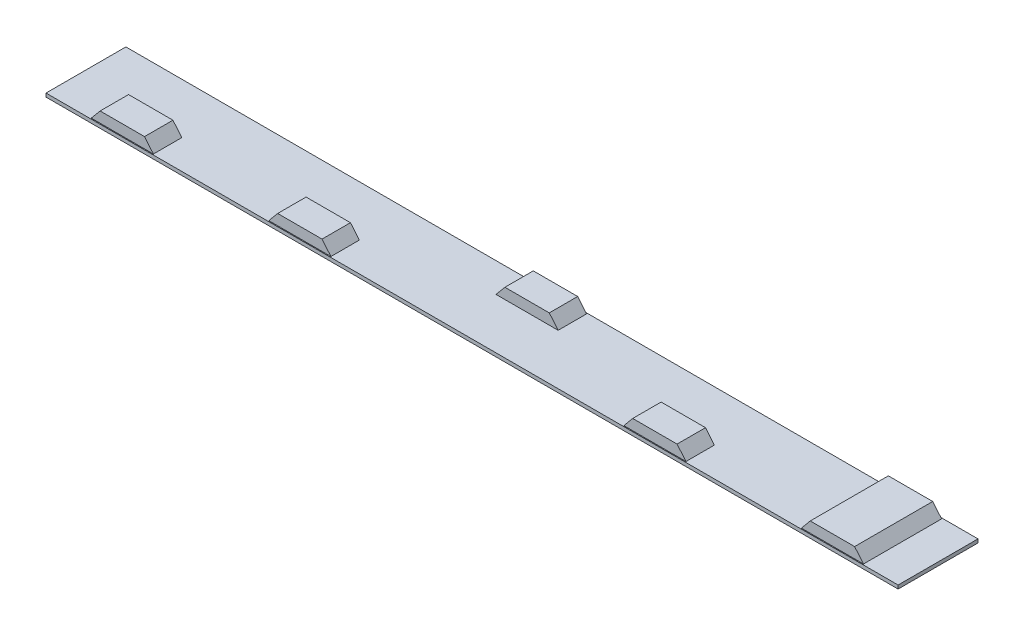
SolidWorks part; units mm, degrees
ref_plane "Front Plane" through (0, 0, 0) normal (0, 0, 1) x (1, 0, 0)
ref_plane "Top Plane" through (0, 0, 0) normal (0, 1, 0) x (1, 0, 0)
ref_plane "Right Plane" through (0, 0, 0) normal (1, 0, 0) x (0, 0, -1)
sketch "Sketch1" plane through (0, 0, 0) normal (0, 1, 0) x (1, 0, 0)
  line L1 (1200, 112.5) -> (-1200, 112.5)
  line L2 (1200, 112.5) -> (1200, -112.5)
  line L3 (1200, -112.5) -> (-1200, -112.5)
  line L4 (-1200, 112.5) -> (-1200, -112.5)
  line L5 (1200, 112.5) -> (-1200, -112.5) construction
  line L6 (1200, -112.5) -> (-1200, 112.5) construction
  point P0 (0, 0)
  dimension "D1" = 2400
  dimension "D2" = 225
extrude "Boss-Extrude1" add sketch "Sketch1" along normal blind 10
sketch "Sketch4" plane through (0, 0, 0) normal (0, 0, 1) x (1, 0, 0)
  line L0 (425, 10) -> (600, 10) construction
  line L1 (-1200, 10) -> (1200, 10) construction
  line L2 (600, 10) -> (575, 40) construction
  line L3 (575, 40) -> (450, 40) construction
  line L4 (450, 40) -> (425, 10) construction
  line L5 (-1075, 10) -> (-900, 10)
  line L6 (-900, 10) -> (-925, 40)
  line L7 (-925, 40) -> (-1050, 40)
  line L8 (-1050, 40) -> (-1075, 10)
  point P4 (512.5, 40)
  point P7 (512.5, 10)
  dimension "D1" = 175
  dimension "D2" = 125
  dimension "D3" = 30
  dimension "D4" = 600
  dimension "D5" = 2
extrude "Boss-Extrude3" add sketch "Sketch4" along normal blind 80 from offset 30
sketch "Sketch5" plane through (0, 0, 0) normal (0, 0, 1) x (1, 0, 0)
  line L0 (-75, 10) -> (100, 10)
  line L1 (100, 10) -> (75, 40)
  line L2 (75, 40) -> (-50, 40)
  line L3 (-50, 40) -> (-75, 10)
  line L4 (-1075, 10) -> (-900, 10)
  line L5 (-1075, 10) -> (-900, 10) construction
  line L6 (-900, 10) -> (-925, 40)
  line L7 (-900, 10) -> (-925, 40) construction
  line L12 (-75, 10) -> (100, 10)
  line L13 (100, 10) -> (75, 40)
  line L14 (75, 40) -> (-50, 40)
  line L15 (-50, 40) -> (-75, 10)
  line L16 (-925, 40) -> (-1050, 40)
  line L17 (-925, 40) -> (-1050, 40) construction
  line L18 (-1050, 40) -> (-1075, 10)
  line L19 (-1050, 40) -> (-1075, 10) construction
  dimension "D1" = 0
  dimension "D2" = 2
sketch "Sketch6" plane through (0, 0, 0) normal (0, 0, 1) x (1, 0, 0)
  line L0 (-50, 40) -> (-75, 10) construction
  line L1 (-75, 10) -> (100, 10) construction
  line L2 (100, 10) -> (75, 40) construction
  line L3 (75, 40) -> (-50, 40) construction
  line L4 (-50, 40) -> (-75, 10) construction
  line L5 (-75, 10) -> (100, 10) construction
  line L6 (100, 10) -> (75, 40) construction
  line L7 (75, 40) -> (-50, 40) construction
  line L8 (-550, 40) -> (-575, 10)
  line L9 (-575, 10) -> (-400, 10)
  line L10 (-400, 10) -> (-425, 40)
  line L11 (-425, 40) -> (-550, 40)
  dimension "D1" = 2
extrude "Boss-Extrude5" add sketch "Sketch6" along normal blind 80 from offset 30
extrude "Boss-Extrude6" add sketch "Sketch5" against normal blind 80 from offset 30 contours L0 L1 L2 L3 offset against normal yes
sketch "Sketch7" plane through (0, 0, 0) normal (0, 0, 1) x (1, 0, 0)
  line L0 (425, 10) -> (600, 10)
  line L1 (600, 10) -> (575, 40)
  line L2 (575, 40) -> (450, 40)
  line L3 (450, 40) -> (425, 10)
  line L4 (-75, 10) -> (100, 10)
  line L5 (100, 10) -> (75, 40)
  line L6 (75, 40) -> (-50, 40)
  line L7 (-50, 40) -> (-75, 10)
  line L8 (-75, 10) -> (100, 10) construction
  line L9 (100, 10) -> (75, 40) construction
  line L10 (75, 40) -> (-50, 40) construction
  line L11 (-50, 40) -> (-75, 10) construction
  line L12 (-75, 10) -> (100, 10)
  line L13 (100, 10) -> (75, 40)
  line L14 (75, 40) -> (-50, 40)
  line L15 (-50, 40) -> (-75, 10)
  line L16 (-75, 10) -> (100, 10) construction
  line L17 (100, 10) -> (75, 40) construction
  line L18 (75, 40) -> (-50, 40) construction
  line L19 (-50, 40) -> (-75, 10) construction
  line L20 (425, 10) -> (600, 10)
  line L21 (600, 10) -> (575, 40)
  line L22 (575, 40) -> (450, 40)
  line L23 (450, 40) -> (425, 10)
  dimension "D1" = 0
  dimension "D2" = 0
  dimension "D3" = 2
extrude "Boss-Extrude7" add sketch "Sketch7" along normal blind 80 from offset 30 contours L2 L3 L0 L1
sketch "Sketch8" plane through (0, 0, 0) normal (0, 0, 1) x (1, 0, 0)
  line L0 (925, 10) -> (1100, 10)
  line L1 (1100, 10) -> (1075, 40)
  line L2 (1075, 40) -> (950, 40)
  line L3 (950, 40) -> (925, 10)
  line L4 (425, 10) -> (600, 10)
  line L5 (600, 10) -> (575, 40)
  line L6 (575, 40) -> (450, 40)
  line L7 (450, 40) -> (425, 10)
  line L8 (425, 10) -> (600, 10) construction
  line L9 (600, 10) -> (575, 40) construction
  line L10 (575, 40) -> (450, 40) construction
  line L11 (450, 40) -> (425, 10) construction
  line L12 (575, 40) -> (450, 40)
  line L13 (450, 40) -> (425, 10)
  line L14 (425, 10) -> (600, 10)
  line L15 (600, 10) -> (575, 40)
  line L16 (575, 40) -> (450, 40) construction
  line L17 (450, 40) -> (425, 10) construction
  line L18 (425, 10) -> (600, 10) construction
  line L19 (600, 10) -> (575, 40) construction
  line L20 (1075, 40) -> (950, 40)
  line L21 (950, 40) -> (925, 10)
  line L22 (925, 10) -> (1100, 10)
  line L23 (1100, 10) -> (1075, 40)
  dimension "D1" = 0
  dimension "D2" = 0
  dimension "D3" = 2
extrude "Boss-Extrude8" add sketch "Sketch8" against normal blind 140 and the other way blind 80 from offset 30 contours L2 L3 L0 L1
